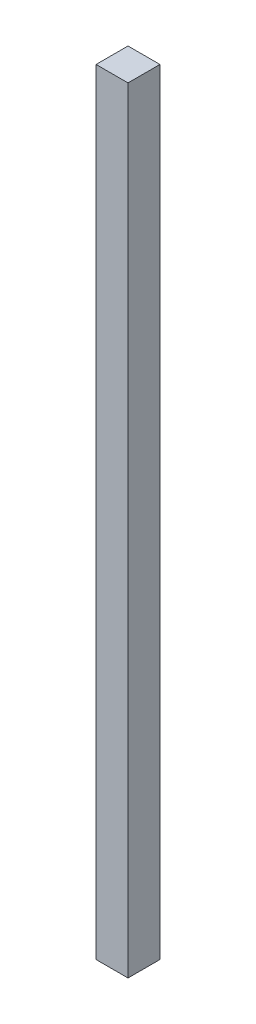
SolidWorks part; units mm, degrees
ref_plane "前视基准面" through (0, 0, 0) normal (0, 0, 1) x (1, 0, 0)
ref_plane "上视基准面" through (0, 0, 0) normal (0, 1, 0) x (1, 0, 0)
ref_plane "右视基准面" through (0, 0, 0) normal (1, 0, 0) x (0, 0, -1)
sketch "草图1" plane through (0, 0, 0) normal (0, 1, 0) x (1, 0, 0)
  line L1 (-15, -15) -> (15, -15)
  line L2 (-15, -15) -> (-15, 15)
  line L3 (-15, 15) -> (15, 15)
  line L4 (15, -15) -> (15, 15)
  line L5 (0, 15) -> (0, -15) construction
  line L6 (-15, 0) -> (15, 0) construction
  point P0 (0, 0)
  dimension "D1" = 30
extrude "凸台-拉伸1" add sketch "草图1" along normal blind 728
